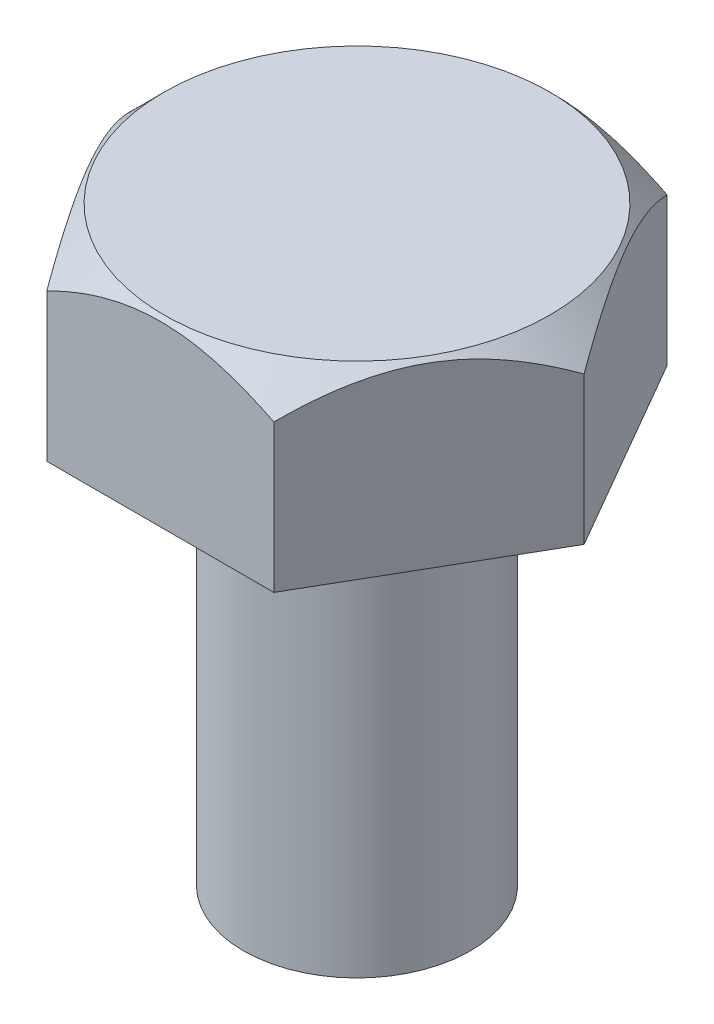
SolidWorks part; units mm, degrees
ref_plane "Front Plane" through (0, 0, 0) normal (0, 0, 1) x (1, 0, 0)
ref_plane "Top Plane" through (0, 0, 0) normal (0, 1, 0) x (1, 0, 0)
ref_plane "Right Plane" through (0, 0, 0) normal (1, 0, 0) x (0, 0, -1)
sketch "Sketch1" plane through (0, 0, 0) normal (0, 1, 0) x (1, 0, 0)
  circle A0 centre (0, 0) radius 2.5
  dimension "D1" = 5
extrude "Boss-Extrude1" add sketch "Sketch1" along normal blind 9
sketch "Sketch2" plane through (0, 9, 0) normal (0, 1, 0) x (1, 0, 0)
  line L0 (0, 2.5) -> (0, -2.5) construction
  line L1 (0, 0) -> (5, 0) construction
  line L2 (-2.5, 4.3301) -> (-5, 0)
  line L3 (-5, 0) -> (-2.5, -4.3301)
  line L4 (-2.5, -4.3301) -> (2.5, -4.3301)
  line L5 (2.5, -4.3301) -> (5, 0)
  line L6 (5, 0) -> (2.5, 4.3301)
  line L7 (2.5, 4.3301) -> (-2.5, 4.3301)
  circle A0 centre (0, 0) radius 2.5 construction
  circle A1 centre (0, 0) radius 4.3301 construction
  dimension "D1" = 10
extrude "Boss-Extrude2" add sketch "Sketch2" along normal blind 4
sketch "Sketch3" plane through (0, 0, 0) normal (0, 0, 1) x (1, 0, 0)
  line L0 (0, 13) -> (0, -0.1937) construction
  line L1 (-2.5, 13) -> (2.5, 13) construction
  line L2 (4.25, 13) -> (5, 13)
  line L3 (2.5, 13) -> (5, 13) construction
  line L4 (5, 13) -> (5, 12.25)
  line L5 (5, 13) -> (5, 9) construction
  line L6 (5, 12.25) -> (4.25, 13)
  point P14 (4.1916, 13)
  dimension "D1" = 0.75
revolve "Cut-Revolve1" cut sketch "Sketch3" angle 360 about L0
